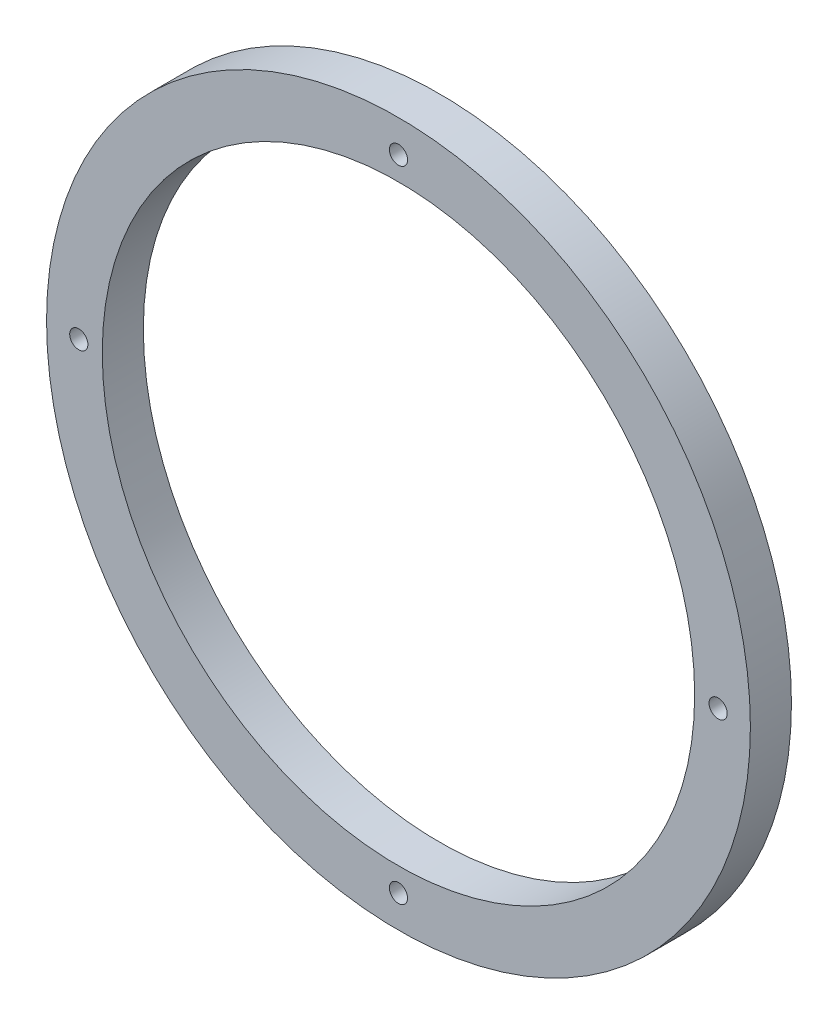
SolidWorks part; units mm, degrees
ref_plane "前视基准面" through (0, 0, 0) normal (0, 0, 1) x (1, 0, 0)
ref_plane "上视基准面" through (0, 0, 0) normal (0, 1, 0) x (1, 0, 0)
ref_plane "右视基准面" through (0, 0, 0) normal (1, 0, 0) x (0, 0, -1)
sketch "草图1" plane through (0, 0, 0) normal (0, 0, 1) x (1, 0, 0)
  circle A0 centre (0, 0) radius 50.5
  circle A1 centre (0, 0) radius 60
extrude "凸台-拉伸1" add sketch "草图1" along normal blind 7
sketch "草图2" plane through (0, 0, 7) normal (0, 0, 1) x (1, 0, 0)
  circle A0 centre (0, 0) radius 54.5 construction
  circle A1 centre (-54.5, 0) radius 1.55
  circle A2 centre (0, 54.5) radius 1.55
  circle A3 centre (54.5, 0) radius 1.55
  circle A4 centre (0, -54.5) radius 1.55
  point P13 (0, 0)
  dimension "D1" = 4
extrude "切除-拉伸1" cut sketch "草图2" against normal blind 7
sketch "草图3" plane through (0, 0, 7) normal (0, 0, 1) x (1, 0, 0)
  circle A0 centre (0, 54.5) radius 1.55 construction
  circle A1 centre (0, 0) radius 60
  circle A2 centre (0, 0) radius 60
  circle A3 centre (-54.5, 0) radius 1.55 construction
  circle A4 centre (0, -54.5) radius 1.55 construction
  circle A5 centre (54.5, 0) radius 1.55 construction
  circle A6 centre (0, 54.5) radius 1.55
  circle A7 centre (-54.5, 0) radius 1.55
  circle A8 centre (0, -54.5) radius 1.55
  circle A9 centre (54.5, 0) radius 1.55
  circle A10 centre (0, 0) radius 50.5 construction
  circle A11 centre (0, 0) radius 50.5
  dimension "D1" = 0
